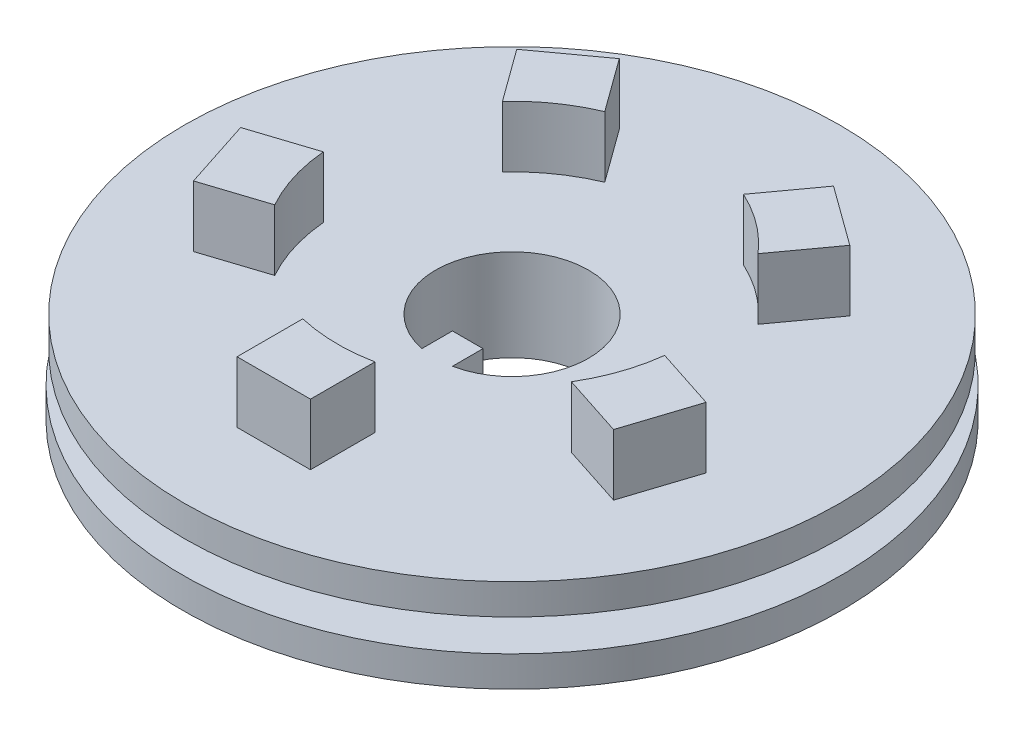
SolidWorks part; units mm, degrees
ref_plane "Front Plane" through (0, 0, 0) normal (1, 0, 0) x (0, 1, 0)
ref_plane "Top Plane" through (0, 0, 0) normal (0, 0, 1) x (0, 1, 0)
ref_plane "Right Plane" through (0, 0, 0) normal (0, 1, 0) x (-1, 0, 0)
sketch "Sketch1" plane through (0, 0, 0) normal (1, 0, 0) x (0, 1, 0)
  line L1 (-5, -22.251) -> (-5, 15.4156)
  line L2 (-5, 15.4156) -> (0, 15.4156)
  line L3 (0, 15.4156) -> (0, 0.1097)
  line L5 (-5, -25.9561) -> (10, -25.9561)
  line L9 (5, 0.1097) -> (5, 15.1097)
  line L10 (5, 15.1097) -> (10, 15.1097)
  line L13 (10, 15.1097) -> (10, 0.1097)
  line L14 (-20, -38.4561) -> (10, -38.4561) construction
  line L15 (2.5, 0.1097) -> (2.5, 50000.1097) construction
  line L16 (-5, -25.9561) -> (-5, -22.251)
  line L17 (10, 0.1097) -> (10, -25.9561)
  line L20 (0, 0.1097) -> (5, 0.1097)
  point P5 (0, 0)
  point P18 (2.5, 0.1097)
  dimension "D1" = 5
  dimension "D2" = 5
  dimension "D3" = 5
  dimension "D4" = 5
  dimension "D5" = 15
  dimension "D6" = 12.5
revolve "Revolve1" add sketch "Sketch1" angle 360 about L14
sketch "Sketch2" plane through (0, 10, 0) normal (0, 1, 0) x (1, 0, 0)
  line L0 (-2.5, 31.2087) -> (2.5, 31.2087)
  line L1 (2.5, 31.2087) -> (2.5, 26.2087)
  line L2 (-2.5, 31.2087) -> (-2.5, 26.2087)
  circle A0 centre (0, 38.4561) radius 12.5 construction
  arc A1 (2.5, 26.2087) -> (-2.5, 26.2087) centre (0, 38.4561) cw
  point P4 (0, 31.2087)
  point P6 (0, 31.2087)
  dimension "D1" = 5
  dimension "D2" = 5
  dimension "D3" = 12.5
  dimension "D4" = 5
extrude "Boss-Extrude1" add sketch "Sketch2" against normal blind 15
sketch "Sketch3" plane through (0, -5, 0) normal (0, -1, 0) x (1, 0, 0)
  line L1 (-2.5, -31.2087) -> (-2.5, -26.2087) construction
  line L2 (-6.4511, 0.0439) -> (5.5489, 0.0439)
  line L4 (2.5, -31.2087) -> (-2.5, -31.2087) construction
  line L5 (-6.4511, 0.0439) -> (-6.4511, -10.6896)
  line L6 (5.5489, 0.0439) -> (5.5489, -10.496)
  line L7 (-0.4511, 0.0439) -> (-0.4511, -9.9561) construction
  circle A2 centre (0, -38.5526) radius 28.6 construction
  arc A3 (-6.4511, -10.6896) -> (5.5489, -10.496) centre (0, -38.5526) cw
  point P10 (-0.4511, 0.0439)
  dimension "D1" = 57.2
  dimension "D2" = 2.5
  dimension "D4" = 12
  dimension "D8" = 10.7335
  dimension "D3" = 5
  dimension "D5" = 5
  dimension "D6" = 10
  dimension "D7" = 31.2526
extrude "Boss-Extrude2" add sketch "Sketch3" along normal blind 10
pattern_circular "CirPattern1" count 5 over 360 about axis through (0, 0, -38.4561) along (0, 1, 0) of "Boss-Extrude2"
ref_plane "Plane3" through (0, 2.5, 0) normal (0, -1, 0) x (0, 0, 1)
mirror "Mirror3" about plane through (0, 2.5, 0) normal (0, -1, 0) of "CirPattern1", "Boss-Extrude2"
